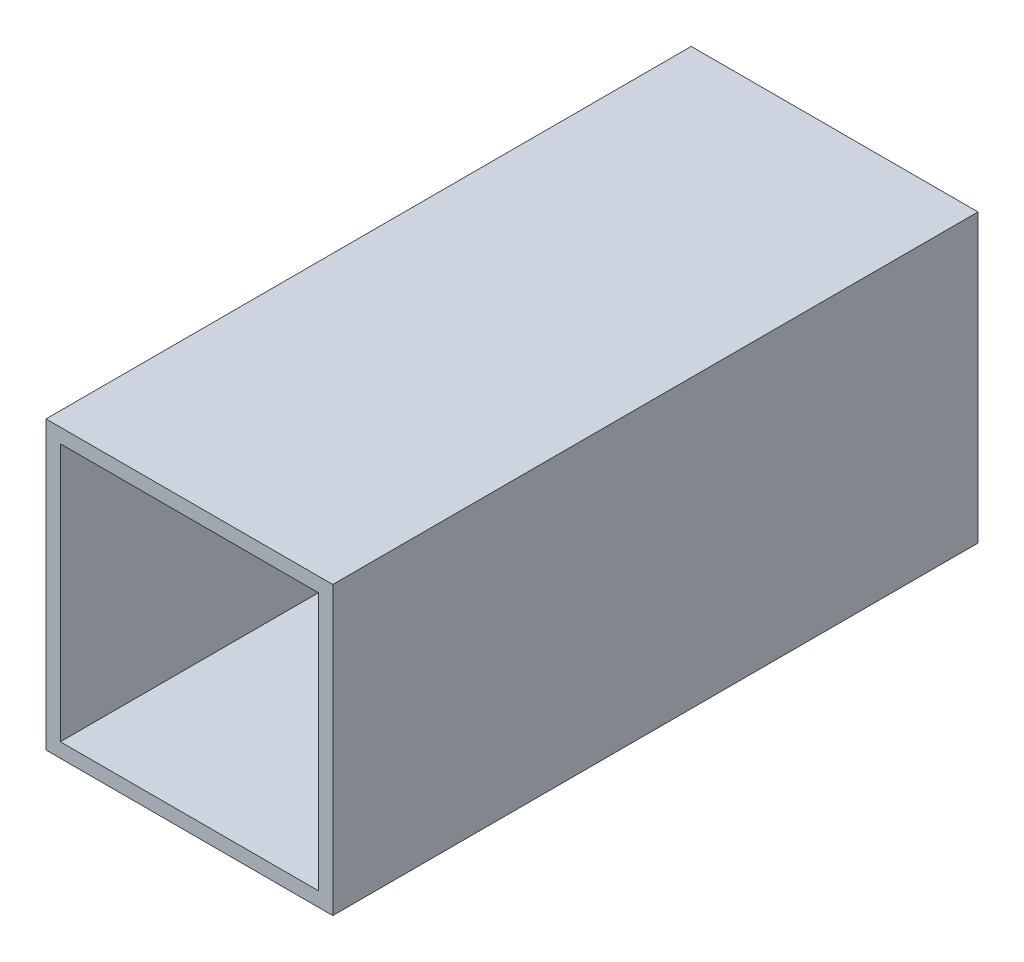
SolidWorks part; units mm, degrees
material "Glass"
ref_plane "Front Plane" through (0, 0, 0) normal (0, 0, 1) x (1, 0, 0)
ref_plane "Top Plane" through (0, 0, 0) normal (0, 1, 0) x (1, 0, 0)
ref_plane "Right Plane" through (0, 0, 0) normal (1, 0, 0) x (0, 0, -1)
sketch "Sketch1" plane through (0, 0, 0) normal (0, 0, 1) x (1, 0, 0)
  line L1 (1.6329, 0) -> (52.4329, 0)
  line L2 (1.6329, 0) -> (1.6329, 50.8)
  line L3 (1.6329, 50.8) -> (52.4329, 50.8)
  line L4 (52.4329, 0) -> (52.4329, 50.8)
  line L5 (4.1729, 2.54) -> (49.8929, 2.54)
  line L6 (4.1729, 2.54) -> (4.1729, 48.26)
  line L7 (4.1729, 48.26) -> (49.8929, 48.26)
  line L8 (49.8929, 2.54) -> (49.8929, 48.26)
  dimension "D1" = 50.8
  dimension "D2" = 50.8
  dimension "D3" = 45.72
  dimension "D4" = 45.72
  dimension "D5" = 2.54
  dimension "D6" = 2.54
extrude "Boss-Extrude1" add sketch "Sketch1" along normal blind 114.3
